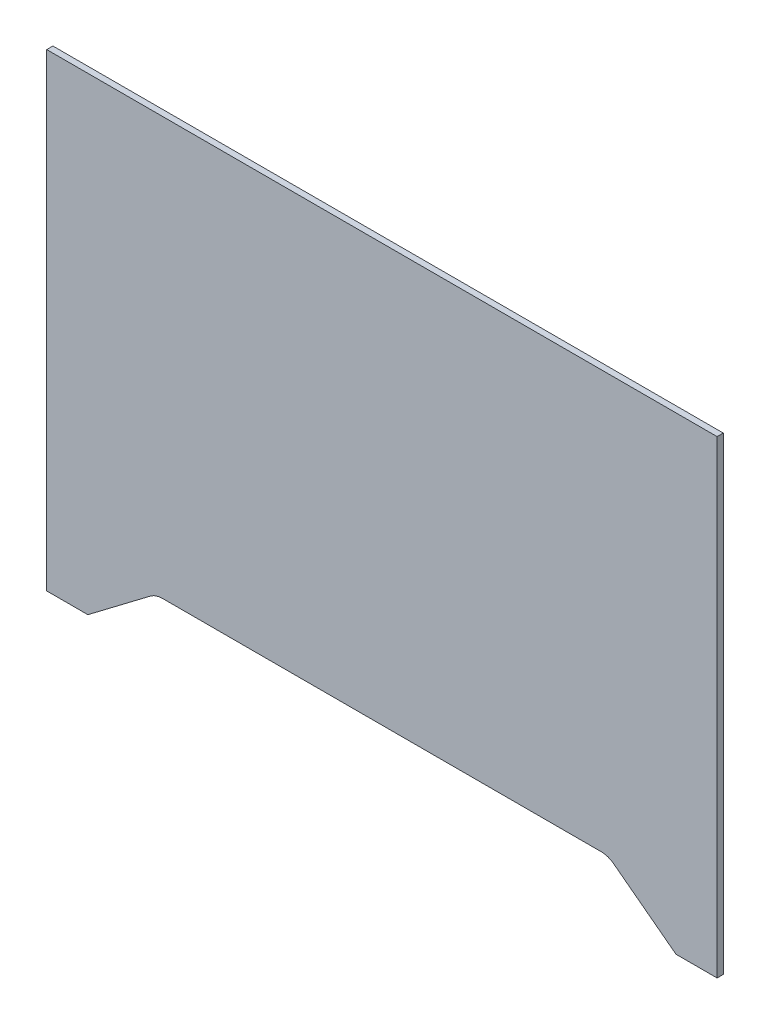
SolidWorks part; units mm, degrees
ref_plane "前视基准面" through (0, 0, 0) normal (0, 0, 1) x (1, 0, 0)
ref_plane "上视基准面" through (0, 0, 0) normal (0, 1, 0) x (1, 0, 0)
ref_plane "右视基准面" through (0, 0, 0) normal (1, 0, 0) x (0, 0, -1)
sketch "Sketch1" plane through (0, 0, 0) normal (0, 0, 1) x (1, 0, 0)
  line L0 (0, -114) -> (0, 0) construction
  line L1 (-163, -114) -> (163, -114) construction
  line L2 (-163, -114) -> (-163, 114)
  line L3 (-163, 114) -> (163, 114)
  line L4 (163, -114) -> (163, 114)
  line L5 (-163, -114) -> (163, 114) construction
  line L6 (-163, 114) -> (163, -114) construction
  line L7 (-106.6398, -89) -> (106.6398, -89)
  line L8 (112.6784, -91.0291) -> (143, -114)
  line L9 (143, -114) -> (163, -114)
  line L10 (-143, -114) -> (-163, -114)
  line L11 (-112.6784, -91.0291) -> (-143, -114)
  arc A0 (112.6784, -91.0291) -> (106.6398, -89) centre (106.6398, -99) ccw
  arc A1 (-112.6784, -91.0291) -> (-106.6398, -89) centre (-106.6398, -99) cw
  point P0 (0, 0)
  point P13 (110, -89)
  point P18 (0, -89)
  dimension "D6" = 10
  dimension "D1" = 326
  dimension "D2" = 228
  dimension "D3" = 25
  dimension "D4" = 20
  dimension "D5" = 110
extrude "Boss-Extrude1" add sketch "Sketch1" along normal blind 3
